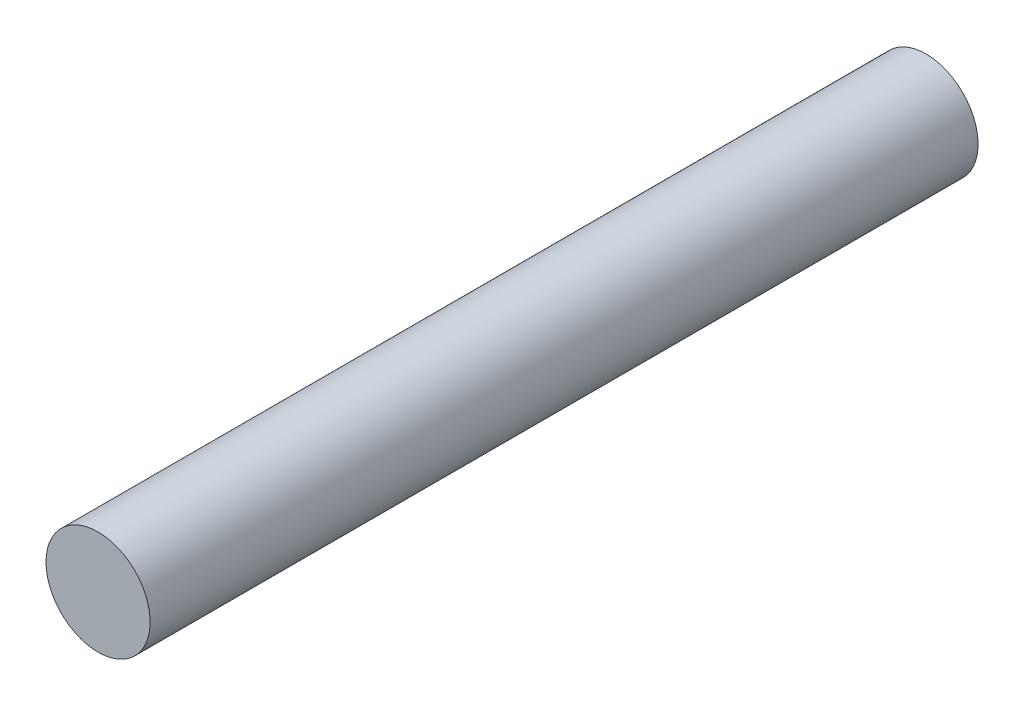
SolidWorks part; units mm, degrees
ref_plane "Front Plane" through (0, 0, 0) normal (0, 0, 1) x (1, 0, 0)
ref_plane "Top Plane" through (0, 0, 0) normal (0, 1, 0) x (1, 0, 0)
ref_plane "Right Plane" through (0, 0, 0) normal (1, 0, 0) x (0, 0, -1)
sketch "Sketch1" plane through (0, 0, 0) normal (0, 0, 1) x (1, 0, 0)
  line L0 (-7.7622, -6.3046) -> (7.7622, 6.3046) construction
  circle A0 centre (0, 0) radius 10
  point P6 (0, 0)
  point P7 (0, 0)
extrude "Boss-Extrude1" add sketch "Sketch1" along normal blind 159
